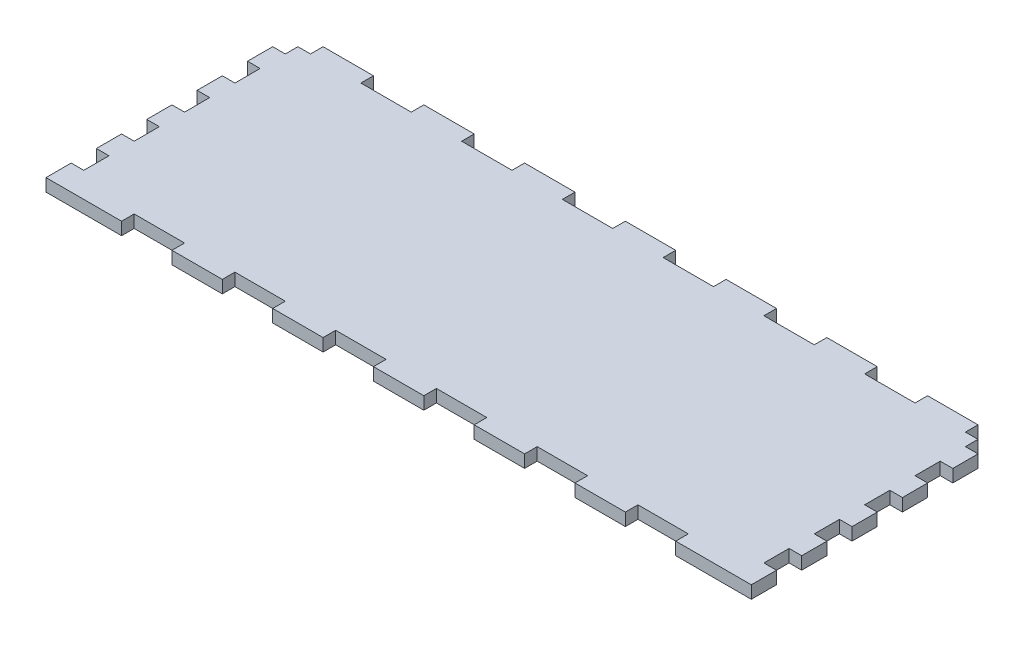
SolidWorks part; units mm, degrees
material "Pin"
ref_plane "Front" through (0, 0, 0) normal (0, 0, 1) x (1, 0, 0)
ref_plane "Top" through (0, 0, 0) normal (0, 1, 0) x (1, 0, 0)
ref_plane "Right" through (0, 0, 0) normal (1, 0, 0) x (0, 0, -1)
sketch "Esquisse1" plane through (0, 0, 0) normal (0, 1, 0) x (1, 0, 0)
  line L1 (-177.8, 63.5) -> (177.8, 63.5)
  line L2 (-177.8, 63.5) -> (-177.8, -63.5)
  line L3 (-177.8, -63.5) -> (177.8, -63.5)
  line L4 (177.8, 63.5) -> (177.8, -63.5)
  line L5 (-177.8, 63.5) -> (177.8, -63.5) construction
  line L6 (-177.8, -63.5) -> (177.8, 63.5) construction
  point P0 (0, 0)
  dimension "D1" = 355.6
  dimension "D2" = 127
extrude "Boss.-Extru.1" add sketch "Esquisse1" along normal blind 6.35
sketch "Esquisse3" plane through (0, 6.35, 0) normal (0, 1, 0) x (1, 0, 0)
  line L0 (177.8, 63.5) -> (-177.8, 63.5) construction
  line L1 (-139.7, 63.5) -> (-114.3, 63.5)
  line L2 (-139.7, 63.5) -> (-139.7, 57.15)
  line L3 (-139.7, 57.15) -> (-114.3, 57.15)
  line L4 (-114.3, 63.5) -> (-114.3, 57.15)
  line L5 (-177.8, 63.5) -> (-177.8, -63.5) construction
  dimension "D1" = 6.35
  dimension "D2" = 25.4
  dimension "D3" = 38.1
extrude "Enlèv. mat.-Extru.2" cut sketch "Esquisse3" against normal blind 6.35
sketch "Esquisse4" plane through (0, 6.35, 0) normal (0, 1, 0) x (1, 0, 0)
  line L0 (-177.8, 63.5) -> (-177.8, -63.5) construction
  line L1 (-177.8, 50.8) -> (-171.45, 50.8)
  line L2 (-177.8, 50.8) -> (-177.8, 63.5)
  line L3 (-177.8, 63.5) -> (-171.45, 63.5)
  line L4 (-171.45, 50.8) -> (-171.45, 63.5)
  line L8 (-139.7, 63.5) -> (-177.8, 63.5) construction
  dimension "D1" = 6.35
  dimension "D2" = 12.7
extrude "Enlèv. mat.-Extru.3" cut sketch "Esquisse4" against normal blind 25.4
pattern_linear "Répétition linéaire1" count 6 spacing 50.8 along (1, 0, 0) count 2 spacing 120.65 along (0, 0, 1) of "Enlèv. mat.-Extru.2"
pattern_linear "Répétition linéaire3" count 5 spacing 25.4 along (0, 0, 1) count 2 spacing 349.25 along (1, 0, 0) of "Enlèv. mat.-Extru.3"
sketch "Esquisse5" plane through (0, 6.35, 0) normal (0, 1, 0) x (1, 0, 0)
  line L0 (-177.8, 50.8) -> (-177.8, 38.1) construction
  line L1 (-177.8, 63.5) -> (-165.1, 63.5)
  line L2 (-177.8, 63.5) -> (-177.8, 57.15)
  line L3 (-177.8, 57.15) -> (-165.1, 57.15)
  line L4 (-165.1, 63.5) -> (-165.1, 57.15)
  line L5 (-139.7, 63.5) -> (-171.45, 63.5) construction
  line L6 (177.8, 38.1) -> (177.8, 50.8) construction
  line L7 (177.8, 63.5) -> (165.1, 63.5)
  line L8 (177.8, 63.5) -> (177.8, 57.15)
  line L9 (177.8, 57.15) -> (165.1, 57.15)
  line L10 (165.1, 63.5) -> (165.1, 57.15)
  line L11 (171.45, 63.5) -> (139.7, 63.5) construction
  line L12 (139.7, 57.15) -> (139.7, 63.5) construction
  dimension "D1" = 6.35
  dimension "D2" = 12.7
  dimension "D3" = 25.4
  dimension "D4" = 6.35
extrude "Enlèv. mat.-Extru.4" cut sketch "Esquisse5" against normal blind 6.35
sketch "Esquisse7" plane through (0, 6.35, 0) normal (0, 1, 0) x (1, 0, 0)
  circle A0 centre (0, 0) radius 44.45
  circle A1 centre (-114.3, 0) radius 44.45
  circle A2 centre (114.3, 0) radius 44.45
  dimension "D3" = 88.9
  dimension "D1" = 114.3
  dimension "D2" = 114.3
